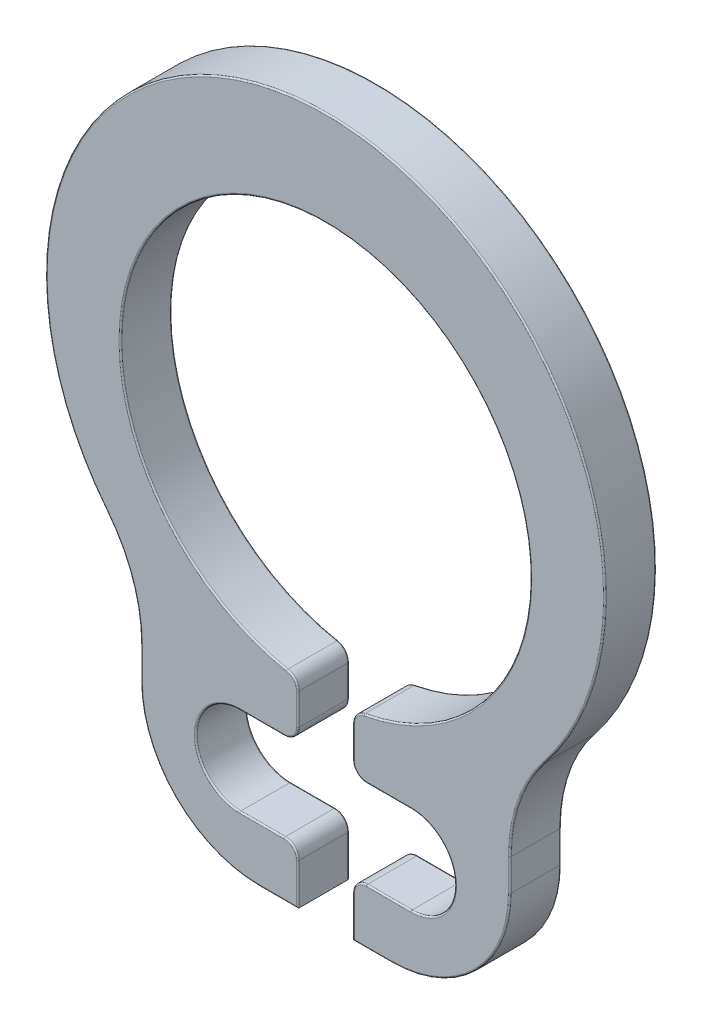
SolidWorks part; units mm, degrees
ref_plane "Front Plane" through (0, 0, 0) normal (0, 0, 1) x (1, 0, 0)
ref_plane "Top Plane" through (0, 0, 0) normal (0, 1, 0) x (1, 0, 0)
ref_plane "Right Plane" through (0, 0, 0) normal (1, 0, 0) x (0, 0, -1)
sketch "Sketch1" plane through (0, 0, 0) normal (0, 0, 1) x (1, 0, 0)
  line L0 (0, 4.8) -> (0, -4.8) construction
  line L1 (-1.17, -3.45) -> (1.17, -3.45) construction
  line L2 (-1.17, -2.85) -> (1.17, -2.85)
  line L3 (-1.17, -4.05) -> (1.17, -4.05)
  line L4 (1.77, -3.45) -> (2.52, -3.45) construction
  line L5 (0, -2.1) -> (0, -2.85) construction
  circle A0 centre (0, 0.7) radius 2.8
  arc A3 (-1.17, -2.85) -> (-1.17, -4.05) centre (-1.17, -3.45) ccw
  arc A4 (1.17, -4.05) -> (1.17, -2.85) centre (1.17, -3.45) ccw
  circle A5 centre (0, 0.98) radius 3.82 construction
  circle A6 centre (0, 0.7) radius 3 construction
  circle A7 centre (0, 0.7) radius 2.85 construction
  point P6 (0, 3.5)
  point P7 (0, -2.1)
  point P10 (0, -3.45)
  dimension "For OD" = 6
  dimension "ID" = 5.6
  dimension "Band Width" = 1.3
  dimension "Tap Height" = 2.7
  dimension "Tap ID" = 1.2
  dimension "D3" = 1.35
  dimension "Tap Width Ref" = 5.04
  dimension "D1" = 0.28
sketch "Sketch2" plane through (0, 0, 0) normal (1, 0, 0) x (0, 0, -1)
  line L0 (-0.35, 4.8) -> (0.35, 4.8) construction
  line L1 (0, 6.2) -> (0, -4.8) construction
  line L2 (0, 4.8) -> (0, -4.8) construction
  line L3 (-0.4, 6.2) -> (0.4, 6.2) construction
  line L4 (-0.4, -4.8) -> (0.4, -4.8) construction
  dimension "Thickness" = 0.7
  dimension "For Groove Width" = 0.8
sketch "Sketch3" plane through (0, 0, 0) normal (0, 0, 1) x (1, 0, 0)
  line L0 (-1.17, -4.05) -> (1.17, -4.05) construction
  line L1 (-1.17, -2.85) -> (1.17, -2.85) construction
  line L2 (-1.17, -4.05) -> (1.17, -4.05)
  line L3 (-1.17, -2.85) -> (1.17, -2.85)
  line L4 (2.52, -2.7462) -> (2.52, -3.18)
  line L5 (-0.9, -4.8) -> (0.9, -4.8)
  line L6 (-2.52, -2.7462) -> (-2.52, -3.18)
  line L7 (-1.77, -3.45) -> (-2.52, -3.45) construction
  line L8 (1.77, -3.45) -> (2.52, -3.45) construction
  arc A0 (-1.17, -2.85) -> (-1.17, -4.05) centre (-1.17, -3.45) ccw construction
  arc A1 (1.17, -4.05) -> (1.17, -2.85) centre (1.17, -3.45) ccw construction
  arc A2 (-1.17, -2.85) -> (-1.17, -4.05) centre (-1.17, -3.45) ccw
  arc A3 (1.17, -4.05) -> (1.17, -2.85) centre (1.17, -3.45) ccw
  circle A4 centre (0, 0.7) radius 2.8 construction
  circle A5 centre (0, 0.7) radius 2.8
  arc A6 (-2.991, -1.3962) -> (2.991, -1.3962) centre (0, 0.98) cw
  arc A8 (2.991, -1.3962) -> (2.52, -2.7462) centre (4.6903, -2.7462) ccw
  arc A9 (2.52, -3.18) -> (0.9, -4.8) centre (0.9, -3.18) cw
  arc A10 (-2.991, -1.3962) -> (-2.52, -2.7462) centre (-4.6903, -2.7462) cw
  arc A11 (-2.52, -3.18) -> (-0.9, -4.8) centre (-0.9, -3.18) ccw
  circle A12 centre (0, 0.98) radius 3.82 construction
  dimension "D1" = 1.35
  dimension "D2" = 1.62
  dimension "D3" = 0.75
extrude "Boss-Extrude1" add sketch "Sketch3" along normal mid plane 0.7
sketch "Sketch4" plane through (0, 0, 0) normal (0, 0, 1) x (1, 0, 0)
  line L0 (0, 0.7) -> (0, -4.8)
extrude "Cut-Extrude-Thin1" cut sketch "Sketch4" against normal through all both and the other way through all thin thin type mid plane wall 0.75
fillet "Fillet2" radius 0.1875 6 edges at (0.375, -4.05, 0) (-0.375, -4.05, 0) (0.375, -2.85, 0) (0.375, -2.0748, 0) (-0.375, -2.85, 0) (-0.375, -2.0748, 0)
fillet "Fillet1" radius 0.02 52 edges at (-0.8662, -4.05, -0.35) (-1.77, -3.45, -0.35) (-0.8662, -2.85, -0.35) (0, 3.5, -0.35) (0.8662, -2.85, -0.35) (1.77, -3.45, -0.35) (0.8663, -4.05, -0.35) (0.375, -4.5188, -0.35) (0.6375, -4.8, -0.35) (2.0455, -4.3255, -0.35) (2.52, -2.9631, -0.35) (2.6411, -2.0313, -0.35) (0, 4.8, -0.35) (-2.6411, -2.0313, -0.35) (-2.52, -2.9631, -0.35) (-2.0455, -4.3255, -0.35) (-0.6375, -4.8, -0.35) (-0.375, -4.5188, -0.35) (-2.0455, -4.3255, 0.35) (-2.52, -2.9631, 0.35) (-2.6411, -2.0313, 0.35) (0, 4.8, 0.35) (2.6411, -2.0313, 0.35) (2.52, -2.9631, 0.35) (2.0455, -4.3255, 0.35) (0.6375, -4.8, 0.35) (0.375, -4.5188, 0.35) (0.8663, -4.05, 0.35) (1.77, -3.45, 0.35) (0.8662, -2.85, 0.35) (0, 3.5, 0.35) (-0.8662, -2.85, 0.35) (-1.77, -3.45, 0.35) (-0.8662, -4.05, 0.35) (-0.375, -4.5188, 0.35) (-0.6375, -4.8, 0.35) (-0.4299, -4.1049, -0.35) (-0.4299, -2.7951, -0.35) (-0.375, -2.4483, -0.35) (-0.418, -2.1146, -0.35) (0.418, -2.1146, -0.35) (0.375, -2.4483, -0.35) (0.4299, -2.7951, -0.35) (0.4299, -4.1049, -0.35) (0.4299, -2.7951, 0.35) (0.375, -2.4483, 0.35) (0.418, -2.1146, 0.35) (-0.418, -2.1146, 0.35) (-0.375, -2.4483, 0.35) (-0.4299, -2.7951, 0.35) (-0.4299, -4.1049, 0.35) (0.4299, -4.1049, 0.35)
equation "\"D3@Sketch1\"=\"Tap Height@Sketch1\"*0.5"
equation "\"D1@Sketch3\"=\"Tap Height@Sketch1\"*0.5"
equation "\"D2@Sketch3\"=\"Tap Height@Sketch1\"*0.6"
equation "\"D1@Boss-Extrude1\" = \"Thickness@Sketch2\""
equation "\"D1@Sketch1\"= \"ID@Sketch1\" * 0.05"
equation "\"D1@Fillet2\"=\"D3@Sketch3\"*0.25"
